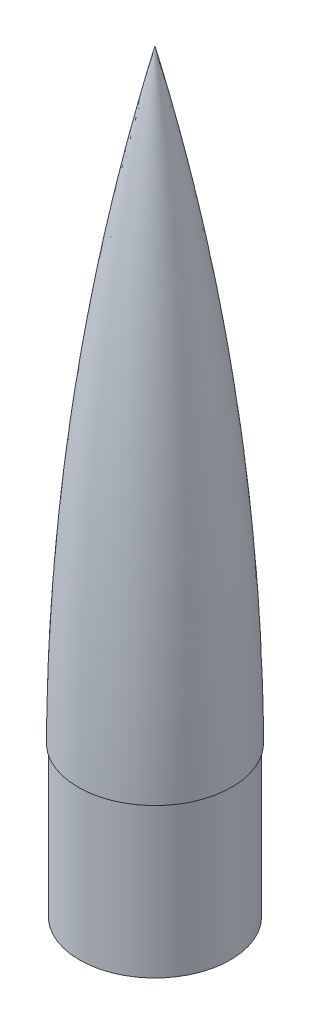
SolidWorks part; units mm, degrees
material "A-Glass Fiber"
ref_plane "Front Plane" through (0, 0, 0) normal (0, 0, 1) x (1, 0, 0)
ref_plane "Top Plane" through (0, 0, 0) normal (0, 1, 0) x (1, 0, 0)
ref_plane "Right Plane" through (0, 0, 0) normal (1, 0, 0) x (0, 0, -1)
sketch "Sketch1" plane through (0, 0, 0) normal (0, 0, 1) x (1, 0, 0)
  line L0 (85.382, 0) -> (-85.382, 0) construction
  line L1 (74.78, 0) -> (76.2, 0)
  line L2 (74.78, 0) -> (74.78, 151.8793)
  line L4 (76.2, 0) -> (76.2, 151.8793)
  line L5 (0, -55) -> (0, 55) construction
  line L6 (76.2, 151.8793) -> (77.62, 151.8793)
  line L7 (0, 761.4793) -> (0, 760.0593)
  line L8 (76.2, 151.8793) -> (77.62, 151.8793)
  arc A0 (77.62, 151.8793) -> (0, 761.4793) centre (-2468.3589, 137.443) ccw
  arc A2 (74.78, 151.8793) -> (0, 760.0593) centre (-2471.3123, 147.5068) ccw
  point P8 (0, 761.4793)
  dimension "D7" = 2546.0198
  dimension "D8" = 2546.096
  dimension "D1" = 1.42
  dimension "D2" = 151.8793
  dimension "D4" = 77.62
  dimension "D5" = 609.6
  dimension "D6" = 1.42
  dimension "D3" = 76.2
ref_axis "Axis1" through (0, 161.7239, 0) along (0, -1, 0)
revolve "Revolve1" add sketch "Sketch1" angle 360 about axis through (0, 161.7239, 0) along (0, -1, 0)
equation "\"exposed length\"= 24in"
equation "\"D5@Sketch1\"=\"exposed length\""
equation "\"shoulder length\"= 5.9795in"
equation "\"shoulder diameter\"= 3in"
equation "\"D2@Sketch1\"=\"shoulder length\""
equation "\"thick\"= 0.055906in"
equation "\"D3@Sketch1\"=\"shoulder diameter\""
equation "\"D1@Sketch1\"=\"thick\""
equation "\"D6@Sketch1\"=\"thick\""
equation "\"D4@Sketch1\"=\"shoulder diameter\"+\"thick\""
